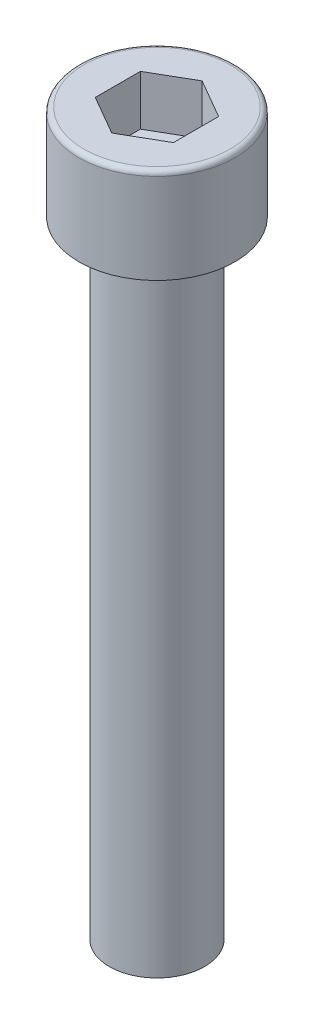
SolidWorks part; units mm, degrees
ref_plane "Front Plane" through (0, 0, 0) normal (0, 0, 1) x (1, 0, 0)
ref_plane "Top Plane" through (0, 0, 0) normal (0, 1, 0) x (1, 0, 0)
ref_plane "Right Plane" through (0, 0, 0) normal (1, 0, 0) x (0, 0, -1)
sketch "Sketch1" plane through (0, 0, 0) normal (0, 1, 0) x (1, 0, 0)
  circle A0 centre (0, 0) radius 2.413
  dimension "D1" = 4.826
extrude "Shaft" add sketch "Sketch1" against normal blind 31.75
sketch "Sketch2" plane through (0, 0, 0) normal (0, 1, 0) x (1, 0, 0)
  circle A0 centre (0, 0) radius 3.9624
  dimension "D1" = 7.9248
extrude "Head" add sketch "Sketch2" along normal blind 4.826
fillet "Fillet1" radius 0.254 1 edges at (0, 4.826, 3.9624)
sketch "Sketch3" plane through (0, 4.826, 0) normal (0, 1, 0) x (1, 0, 0)
  line L1 (0, 2.2914) -> (-1.9844, 1.1457)
  line L2 (-1.9844, 1.1457) -> (-1.9844, -1.1457)
  line L3 (-1.9844, -1.1457) -> (0, -2.2914)
  line L4 (0, -2.2914) -> (1.9844, -1.1457)
  line L5 (1.9844, -1.1457) -> (1.9844, 1.1457)
  line L6 (1.9844, 1.1457) -> (0, 2.2914)
  circle A0 centre (0, 0) radius 1.9844 construction
  dimension "D1" = 3.9688
extrude "Hex" cut sketch "Sketch3" against normal blind 2.54
